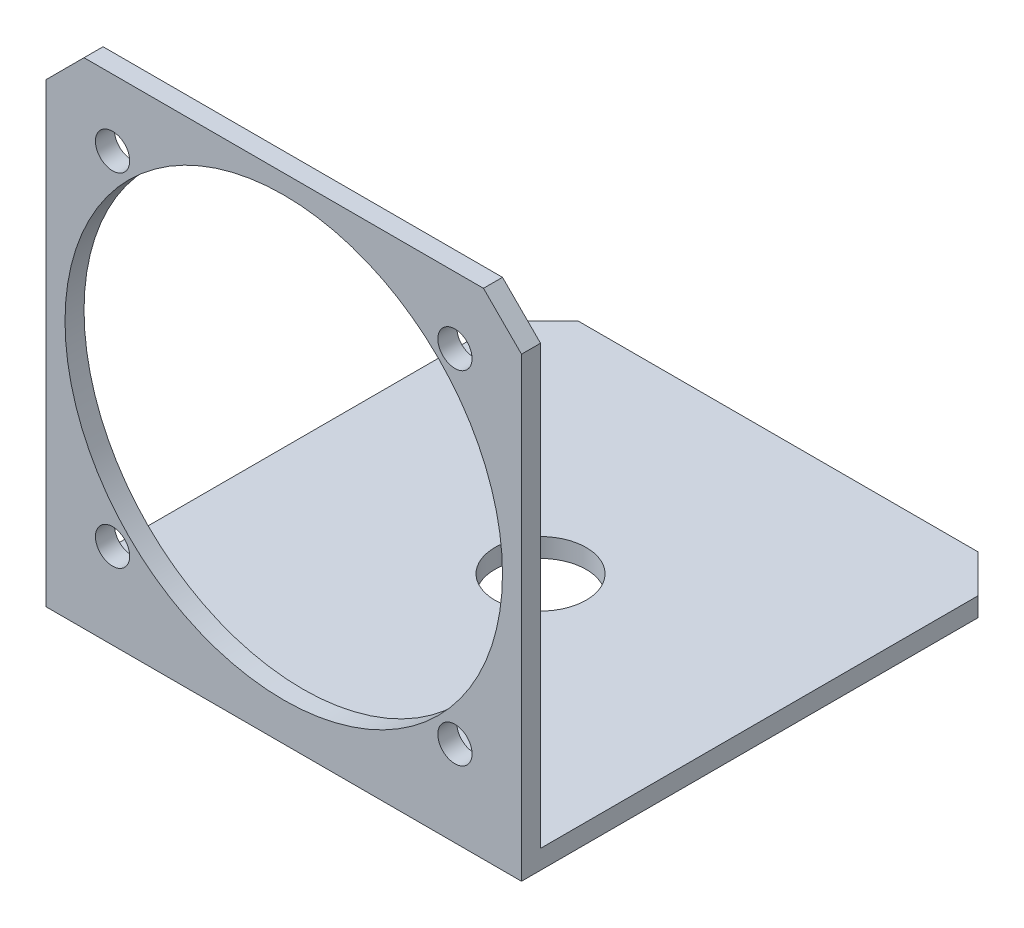
SolidWorks part; units mm, degrees
ref_plane "Front Plane" through (0, 0, 0) normal (0, 0, 1) x (1, 0, 0)
ref_plane "Top Plane" through (0, 0, 0) normal (0, 1, 0) x (1, 0, 0)
ref_plane "Right Plane" through (0, 0, 0) normal (1, 0, 0) x (0, 0, -1)
sketch "Sketch1" plane through (0, 0, 0) normal (0, 0, 1) x (1, 0, 0)
  line L1 (-15.875, -15.875) -> (15.875, -15.875)
  line L2 (-15.875, -15.875) -> (-15.875, 15.875)
  line L3 (-15.875, 15.875) -> (15.875, 15.875)
  line L4 (15.875, -15.875) -> (15.875, 15.875)
  line L5 (-15.875, -15.875) -> (15.875, 15.875) construction
  line L6 (-15.875, 15.875) -> (15.875, -15.875) construction
  circle A0 centre (-11.43, 11.43) radius 1.143
  circle A1 centre (11.43, 11.43) radius 1.143
  circle A2 centre (-11.43, -11.43) radius 1.143
  circle A3 centre (11.43, -11.43) radius 1.143
  circle A4 centre (0, 0) radius 14.605
  point P0 (0, 0)
  dimension "D3" = 2.286
  dimension "D6" = 29.21
  dimension "D1" = 31.75
  dimension "D2" = 31.75
  dimension "D4" = 22.86
  dimension "D5" = 22.86
extrude "Boss-Extrude1" add sketch "Sketch1" along normal blind 1.27
chamfer "Chamfer1" distance 2.54 angle 45 2 edges at (-15.875, 15.875, 0.635) (15.875, 15.875, 0.635)
sketch "Sketch2" plane through (0, -15.875, 0) normal (0, -1, 0) x (1, 0, 0)
  line L0 (-15.875, 1.27) -> (-15.875, 0) construction
  line L1 (15.875, 1.27) -> (-15.875, 1.27)
  line L2 (15.875, 1.27) -> (15.875, -31.75)
  line L3 (15.875, -31.75) -> (-15.875, -31.75)
  line L4 (-15.875, 1.27) -> (-15.875, -31.75)
  line L5 (-15.875, 0) -> (15.875, 0) construction
  dimension "D1" = 31.75
extrude "Boss-Extrude2" add sketch "Sketch2" along normal blind 1.27
sketch "Sketch3" plane through (0, -15.875, 0) normal (0, 1, 0) x (1, 0, 0)
  line L0 (-15.875, 31.75) -> (15.875, 0) construction
  circle A0 centre (0, 15.875) radius 3.048
  point P6 (0, 0)
  dimension "D1" = 6.096
extrude "Cut-Extrude1" cut sketch "Sketch3" against normal blind 1.27
chamfer "Chamfer2" distance 2.54 angle 45 2 edges at (15.875, -16.51, -31.75) (-15.875, -16.51, -31.75)
